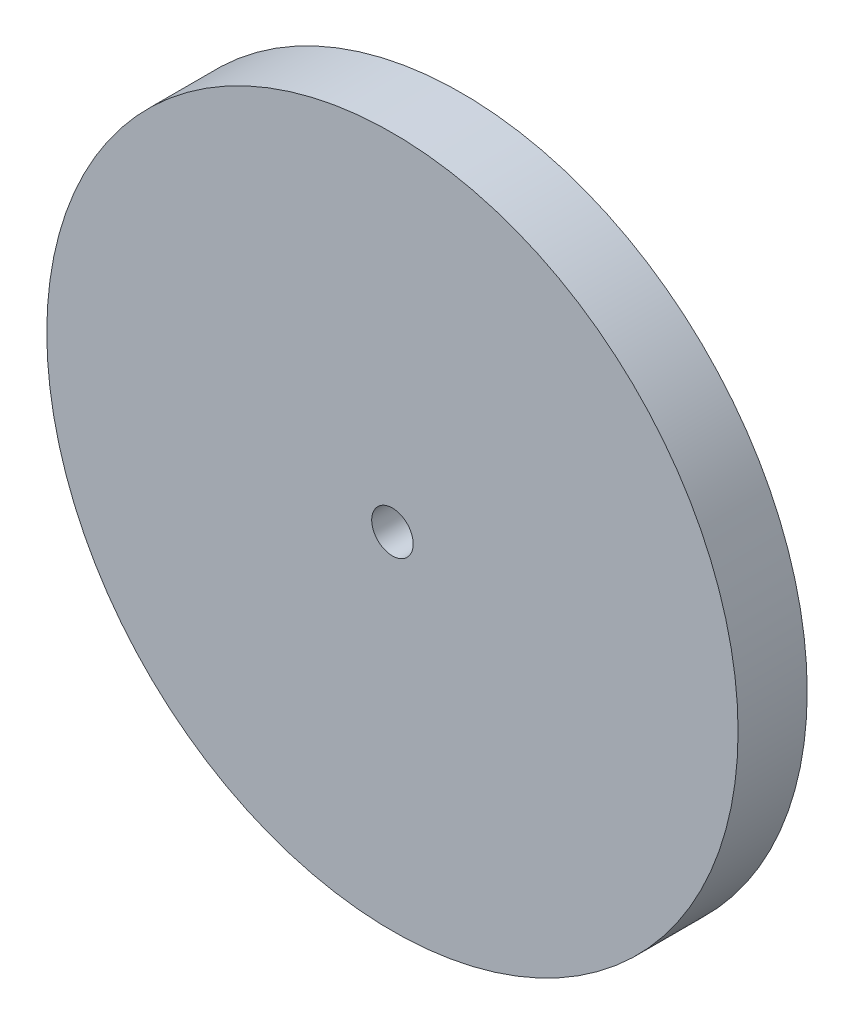
SolidWorks part; units mm, degrees
ref_plane "Front Plane" through (0, 0, 0) normal (0, 0, 1) x (1, 0, 0)
ref_plane "Top Plane" through (0, 0, 0) normal (0, 1, 0) x (1, 0, 0)
ref_plane "Right Plane" through (0, 0, 0) normal (1, 0, 0) x (0, 0, -1)
sketch "Sketch1" plane through (0, 0, 0) normal (0, 0, 1) x (1, 0, 0)
  circle A0 centre (0, 0) radius 3
  circle A1 centre (0, 0) radius 50
  dimension "D1" = 6
  dimension "D2" = 100
extrude "Boss-Extrude2" add sketch "Sketch1" along normal blind 10 contours A1 | A0
